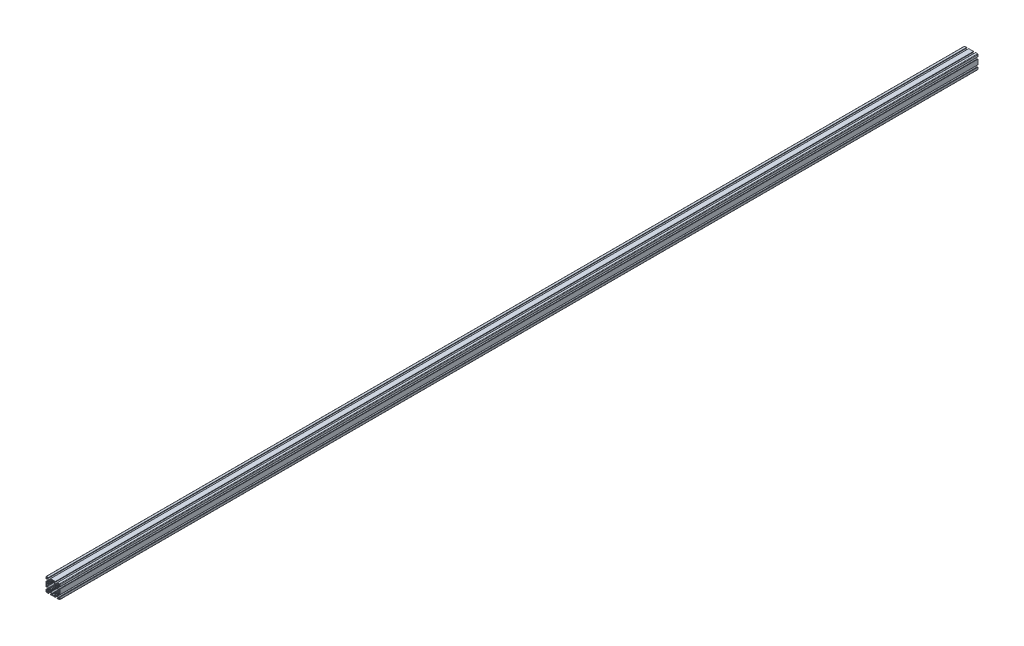
SolidWorks part; units mm, degrees
material "6105-T5 Aluminum"
ref_plane "Front Plane" through (0, 0, 0) normal (0, 0, 1) x (1, 0, 0)
ref_plane "Top Plane" through (0, 0, 0) normal (0, 1, 0) x (1, 0, 0)
ref_plane "Right Plane" through (0, 0, 0) normal (1, 0, 0) x (0, 0, -1)
sketch "Sketch1" plane through (0, 0, 0) normal (0, 0, 1) x (1, 0, 0)
  line L0 (-13.319, -39.4999) -> (-9.88, -39.4999)
  line L1 (-9.5, -39.8799) -> (-9.5, -43.3189)
  line L2 (-9.881, -43.6999) -> (-12.7, -43.6999)
  line L3 (-13.7, -42.6999) -> (-13.7, -39.8809)
  line L4 (39.4999, -43.3189) -> (39.4999, -39.8799)
  line L5 (39.8799, -39.4999) -> (43.3189, -39.4999)
  line L6 (43.6999, -39.8809) -> (43.6999, -42.6999)
  line L7 (42.6999, -43.6999) -> (39.8809, -43.6999)
  line L8 (39.8809, 13.7) -> (42.6999, 13.7)
  line L9 (43.6999, 12.7) -> (43.6999, 9.881)
  line L10 (43.3189, 9.5) -> (39.8799, 9.5)
  line L11 (39.4999, 9.88) -> (39.4999, 13.319)
  line L12 (-9.5, 13.319) -> (-9.5, 9.88)
  line L13 (-9.88, 9.5) -> (-13.319, 9.5)
  line L14 (-13.7, 9.881) -> (-13.7, 12.7)
  line L15 (-12.7, 13.7) -> (-9.881, 13.7)
  line L16 (-1.4942, -3.1981) -> (-2.4733, -3.9799)
  line L17 (-3.9799, -2.4733) -> (-3.1981, -1.4942)
  line L18 (-3.1981, 1.4942) -> (-3.9799, 2.4733)
  line L19 (-2.4733, 3.9799) -> (-1.4942, 3.1981)
  line L20 (1.4942, 3.1981) -> (2.4733, 3.9799)
  line L21 (3.9799, 2.4733) -> (3.1981, 1.4942)
  line L22 (3.1981, -1.4942) -> (3.9799, -2.4733)
  line L23 (2.4733, -3.9799) -> (1.4942, -3.1981)
  line L24 (28.5057, -3.1981) -> (27.5266, -3.9799)
  line L25 (26.02, -2.4733) -> (26.8018, -1.4942)
  line L26 (26.8018, 1.4942) -> (26.02, 2.4733)
  line L27 (27.5266, 3.9799) -> (28.5057, 3.1981)
  line L28 (31.4942, 3.1981) -> (32.4733, 3.9799)
  line L29 (33.9799, 2.4733) -> (33.1981, 1.4942)
  line L30 (33.1981, -1.4942) -> (33.9799, -2.4733)
  line L31 (32.4733, -3.9799) -> (31.4942, -3.1981)
  line L32 (-1.4942, -33.1981) -> (-2.4733, -33.9799)
  line L33 (-3.9799, -32.4733) -> (-3.1981, -31.4942)
  line L34 (-3.1981, -28.5057) -> (-3.9799, -27.5266)
  line L35 (-2.4733, -26.02) -> (-1.4942, -26.8018)
  line L36 (1.4942, -26.8018) -> (2.4733, -26.02)
  line L37 (3.9799, -27.5266) -> (3.1981, -28.5057)
  line L38 (3.1981, -31.4942) -> (3.9799, -32.4733)
  line L39 (2.4733, -33.9799) -> (1.4942, -33.1981)
  line L40 (28.5057, -33.1981) -> (27.5266, -33.9799)
  line L41 (26.02, -32.4733) -> (26.8018, -31.4942)
  line L42 (26.8018, -28.5057) -> (26.02, -27.5266)
  line L43 (27.5266, -26.02) -> (28.5057, -26.8018)
  line L44 (31.4942, -26.8018) -> (32.4733, -26.02)
  line L45 (33.9799, -27.5266) -> (33.1981, -28.5057)
  line L46 (33.1981, -31.4942) -> (33.9799, -32.4733)
  line L47 (32.4733, -33.9799) -> (31.4942, -33.1981)
  line L48 (42.7999, -10.95) -> (42.7999, -19.05)
  line L49 (42.2999, -19.55) -> (39.2681, -19.55)
  line L50 (38.2075, -19.9893) -> (34.178, -24.0188)
  line L51 (33.8244, -24.1653) -> (30.9499, -24.1653)
  line L52 (30.9499, -24.1653) -> (29.9999, -24.6753)
  line L53 (29.9999, -24.6753) -> (29.0499, -24.1653)
  line L54 (29.0499, -24.1653) -> (26.1653, -24.1653)
  line L55 (24.1653, -26.1653) -> (24.1653, -29.1124)
  line L56 (24.1653, -29.1124) -> (24.6753, -30.0624)
  line L57 (24.6753, -30.0624) -> (24.1653, -31.0124)
  line L58 (24.1653, -31.0124) -> (24.1653, -33.8244)
  line L59 (24.0188, -34.178) -> (19.9893, -38.2075)
  line L60 (19.55, -39.2681) -> (19.55, -42.2999)
  line L61 (19.05, -42.7999) -> (10.95, -42.7999)
  line L62 (10.45, -42.2999) -> (10.45, -39.2681)
  line L63 (10.0106, -38.2075) -> (5.9811, -34.178)
  line L64 (5.8347, -33.8244) -> (5.8347, -31.0124)
  line L65 (5.8347, -31.0124) -> (5.3247, -30.0624)
  line L66 (5.3247, -30.0624) -> (5.8347, -29.1124)
  line L67 (5.8347, -29.1124) -> (5.8347, -26.1653)
  line L68 (3.8347, -24.1653) -> (0.95, -24.1653)
  line L69 (0.95, -24.1653) -> (0, -24.6753)
  line L70 (0, -24.6753) -> (-0.95, -24.1653)
  line L71 (-0.95, -24.1653) -> (-3.8245, -24.1653)
  line L72 (-4.178, -24.0188) -> (-8.2075, -19.9893)
  line L73 (-9.2682, -19.55) -> (-12.3, -19.55)
  line L74 (-12.8, -19.05) -> (-12.8, -10.95)
  line L75 (-12.3, -10.45) -> (-9.2682, -10.45)
  line L76 (-8.2075, -10.0106) -> (-4.178, -5.9811)
  line L77 (-3.8245, -5.8347) -> (-0.95, -5.8347)
  line L78 (-0.95, -5.8347) -> (0, -5.3247)
  line L79 (0, -5.3247) -> (0.95, -5.8347)
  line L80 (0.95, -5.8347) -> (3.8347, -5.8347)
  line L81 (5.8347, -3.8347) -> (5.8347, -1.0125)
  line L82 (5.8347, -1.0125) -> (5.3247, -0.0625)
  line L83 (5.3247, -0.0625) -> (5.8347, 0.8875)
  line L84 (5.8347, 0.8875) -> (5.8347, 3.8245)
  line L85 (5.9811, 4.178) -> (10.0106, 8.2075)
  line L86 (10.45, 9.2682) -> (10.45, 12.3)
  line L87 (10.95, 12.8) -> (19.05, 12.8)
  line L88 (19.55, 12.3) -> (19.55, 9.2682)
  line L89 (19.9893, 8.2075) -> (24.0188, 4.178)
  line L90 (24.1653, 3.8245) -> (24.1653, 0.8875)
  line L91 (24.1653, 0.8875) -> (24.6753, -0.0625)
  line L92 (24.6753, -0.0625) -> (24.1653, -1.0125)
  line L93 (24.1653, -1.0125) -> (24.1653, -3.8347)
  line L94 (26.1653, -5.8347) -> (29.0499, -5.8347)
  line L95 (29.0499, -5.8347) -> (29.9999, -5.3247)
  line L96 (29.9999, -5.3247) -> (30.9499, -5.8347)
  line L97 (30.9499, -5.8347) -> (33.8244, -5.8347)
  line L98 (34.178, -5.9811) -> (38.2075, -10.0106)
  line L99 (39.2681, -10.45) -> (42.2999, -10.45)
  line L100 (-14.5, -25.9999) -> (-13.2425, -25.9999)
  line L101 (-12.7425, -25.4999) -> (-12.7425, -22.2674)
  line L102 (-12.2428, -21.75) -> (-10.2602, -21.75)
  line L103 (-9.9067, -21.8964) -> (-5.9811, -25.8219)
  line L104 (-5.8347, -26.1755) -> (-5.8347, -29.1124)
  line L105 (-5.8347, -29.1124) -> (-5.3247, -30.0624)
  line L106 (-5.3247, -30.0624) -> (-5.8347, -31.0124)
  line L107 (-5.8347, -31.0124) -> (-5.8347, -33.8244)
  line L108 (-5.9811, -34.178) -> (-9.9067, -38.1035)
  line L109 (-10.2602, -38.2499) -> (-12.2428, -38.2499)
  line L110 (-12.7425, -37.7325) -> (-12.7425, -34.4999)
  line L111 (-13.2425, -33.9999) -> (-14.5, -33.9999)
  line L112 (-15, -34.4999) -> (-15, -42.9999)
  line L113 (-13, -44.9999) -> (-4.5, -44.9999)
  line L114 (-4, -44.4999) -> (-4, -43.2424)
  line L115 (-4.5, -42.7424) -> (-7.7325, -42.7424)
  line L116 (-8.25, -42.2427) -> (-8.25, -40.2601)
  line L117 (-8.1035, -39.9066) -> (-4.178, -35.9811)
  line L118 (-3.8245, -35.8346) -> (-0.95, -35.8346)
  line L119 (-0.95, -35.8346) -> (0, -35.3246)
  line L120 (0, -35.3246) -> (0.95, -35.8346)
  line L121 (0.95, -35.8346) -> (3.8245, -35.8346)
  line L122 (4.178, -35.9811) -> (8.1035, -39.9066)
  line L123 (8.25, -40.2601) -> (8.25, -42.2427)
  line L124 (7.7325, -42.7424) -> (4.5, -42.7424)
  line L125 (4, -43.2424) -> (4, -44.4999)
  line L126 (4.5, -44.9999) -> (25.4999, -44.9999)
  line L127 (25.9999, -44.4999) -> (25.9999, -43.2424)
  line L128 (25.4999, -42.7424) -> (22.2674, -42.7424)
  line L129 (21.75, -42.2427) -> (21.75, -40.2601)
  line L130 (21.8964, -39.9066) -> (25.8219, -35.9811)
  line L131 (26.1755, -35.8346) -> (29.0499, -35.8346)
  line L132 (29.0499, -35.8346) -> (29.9999, -35.3246)
  line L133 (29.9999, -35.3246) -> (30.9499, -35.8346)
  line L134 (30.9499, -35.8346) -> (33.8244, -35.8346)
  line L135 (34.178, -35.9811) -> (38.1035, -39.9066)
  line L136 (38.2499, -40.2601) -> (38.2499, -42.2427)
  line L137 (37.7325, -42.7424) -> (34.4999, -42.7424)
  line L138 (33.9999, -43.2424) -> (33.9999, -44.4999)
  line L139 (34.4999, -44.9999) -> (42.9999, -44.9999)
  line L140 (44.9999, -42.9999) -> (44.9999, -34.4999)
  line L141 (44.4999, -33.9999) -> (43.2424, -33.9999)
  line L142 (42.7424, -34.4999) -> (42.7424, -37.7325)
  line L143 (42.2427, -38.2499) -> (40.2601, -38.2499)
  line L144 (39.9066, -38.1035) -> (35.9811, -34.178)
  line L145 (35.8346, -33.8244) -> (35.8346, -31.0124)
  line L146 (35.8346, -31.0124) -> (35.3246, -30.0624)
  line L147 (35.3246, -30.0624) -> (35.8346, -29.1124)
  line L148 (35.8346, -29.1124) -> (35.8346, -26.1755)
  line L149 (35.9811, -25.8219) -> (39.9066, -21.8964)
  line L150 (40.2601, -21.75) -> (42.2427, -21.75)
  line L151 (42.7424, -22.2674) -> (42.7424, -25.4999)
  line L152 (43.2424, -25.9999) -> (44.4999, -25.9999)
  line L153 (44.9999, -25.4999) -> (44.9999, -4.5)
  line L154 (44.4999, -4) -> (43.2424, -4)
  line L155 (42.7424, -4.5) -> (42.7424, -7.7325)
  line L156 (42.2427, -8.25) -> (40.2601, -8.25)
  line L157 (39.9066, -8.1035) -> (35.9811, -4.178)
  line L158 (35.8346, -3.8245) -> (35.8346, -1.0125)
  line L159 (35.8346, -1.0125) -> (35.3246, -0.0625)
  line L160 (35.3246, -0.0625) -> (35.8346, 0.8875)
  line L161 (35.8346, 0.8875) -> (35.8346, 3.8245)
  line L162 (35.9811, 4.178) -> (39.9066, 8.1035)
  line L163 (40.2601, 8.25) -> (42.2427, 8.25)
  line L164 (42.7424, 7.7325) -> (42.7424, 4.5)
  line L165 (43.2424, 4) -> (44.4999, 4)
  line L166 (44.9999, 4.5) -> (44.9999, 13)
  line L167 (42.9999, 15) -> (34.4999, 15)
  line L168 (33.9999, 14.5) -> (33.9999, 13.2425)
  line L169 (34.4999, 12.7425) -> (37.7325, 12.7425)
  line L170 (38.2499, 12.2428) -> (38.2499, 10.2602)
  line L171 (38.1035, 9.9067) -> (34.178, 5.9811)
  line L172 (33.8244, 5.8347) -> (30.9499, 5.8347)
  line L173 (30.9499, 5.8347) -> (29.9999, 5.3247)
  line L174 (29.9999, 5.3247) -> (29.0499, 5.8347)
  line L175 (29.0499, 5.8347) -> (26.1755, 5.8347)
  line L176 (25.8219, 5.9811) -> (21.8964, 9.9067)
  line L177 (21.75, 10.2602) -> (21.75, 12.2428)
  line L178 (22.2674, 12.7425) -> (25.4999, 12.7425)
  line L179 (25.9999, 13.2425) -> (25.9999, 14.5)
  line L180 (25.4999, 15) -> (4.5, 15)
  line L181 (4, 14.5) -> (4, 13.2425)
  line L182 (4.5, 12.7425) -> (7.7325, 12.7425)
  line L183 (8.25, 12.2428) -> (8.25, 10.2602)
  line L184 (8.1035, 9.9067) -> (4.178, 5.9811)
  line L185 (3.8245, 5.8347) -> (0.95, 5.8347)
  line L186 (0.95, 5.8347) -> (0, 5.3247)
  line L187 (0, 5.3247) -> (-0.95, 5.8347)
  line L188 (-0.95, 5.8347) -> (-3.8245, 5.8347)
  line L189 (-4.178, 5.9811) -> (-8.1035, 9.9067)
  line L190 (-8.25, 10.2602) -> (-8.25, 12.2428)
  line L191 (-7.7325, 12.7425) -> (-4.5, 12.7425)
  line L192 (-4, 13.2425) -> (-4, 14.5)
  line L193 (-4.5, 15) -> (-13, 15)
  line L194 (-15, 13) -> (-15, 4.5)
  line L195 (-14.5, 4) -> (-13.2425, 4)
  line L196 (-12.7425, 4.5) -> (-12.7425, 7.7325)
  line L197 (-12.2428, 8.25) -> (-10.2602, 8.25)
  line L198 (-9.9067, 8.1035) -> (-5.9811, 4.178)
  line L199 (-5.8347, 3.8245) -> (-5.8347, 0.8875)
  line L200 (-5.8347, 0.8875) -> (-5.3247, -0.0625)
  line L201 (-5.3247, -0.0625) -> (-5.8347, -1.0125)
  line L202 (-5.8347, -1.0125) -> (-5.8347, -3.8245)
  line L203 (-5.9811, -4.178) -> (-9.9067, -8.1035)
  line L204 (-10.2602, -8.25) -> (-12.2428, -8.25)
  line L205 (-12.7425, -7.7325) -> (-12.7425, -4.5)
  line L206 (-13.2425, -4) -> (-14.5, -4)
  line L207 (-15, -4.5) -> (-15, -25.4999)
  arc A0 (-13.319, -39.4999) -> (-13.7, -39.8809) centre (-13.319, -39.8809) ccw
  arc A1 (-9.5, -39.8799) -> (-9.88, -39.4999) centre (-9.88, -39.8799) ccw
  arc A2 (-9.881, -43.6999) -> (-9.5, -43.3189) centre (-9.881, -43.3189) ccw
  arc A3 (-13.7, -42.6999) -> (-12.7, -43.6999) centre (-12.7, -42.6999) ccw
  arc A4 (39.4999, -43.3189) -> (39.8809, -43.6999) centre (39.8809, -43.3189) ccw
  arc A5 (39.8799, -39.4999) -> (39.4999, -39.8799) centre (39.8799, -39.8799) ccw
  arc A6 (43.6999, -39.8809) -> (43.3189, -39.4999) centre (43.3189, -39.8809) ccw
  arc A7 (42.6999, -43.6999) -> (43.6999, -42.6999) centre (42.6999, -42.6999) ccw
  arc A8 (39.8809, 13.7) -> (39.4999, 13.319) centre (39.8809, 13.319) ccw
  arc A9 (43.6999, 12.7) -> (42.6999, 13.7) centre (42.6999, 12.7) ccw
  arc A10 (43.3189, 9.5) -> (43.6999, 9.881) centre (43.3189, 9.881) ccw
  arc A11 (39.4999, 9.88) -> (39.8799, 9.5) centre (39.8799, 9.88) ccw
  arc A12 (-9.5, 13.319) -> (-9.881, 13.7) centre (-9.881, 13.319) ccw
  arc A13 (-9.88, 9.5) -> (-9.5, 9.88) centre (-9.88, 9.88) ccw
  arc A14 (-13.7, 9.881) -> (-13.319, 9.5) centre (-13.319, 9.881) ccw
  arc A15 (-12.7, 13.7) -> (-13.7, 12.7) centre (-12.7, 12.7) ccw
  arc A16 (-1.4942, -3.1981) -> (1.4942, -3.1981) centre (0, 0) ccw
  arc A17 (-3.9799, -2.4733) -> (-2.4733, -3.9799) centre (-3.1422, -3.1422) ccw
  arc A18 (-3.1981, 1.4942) -> (-3.1981, -1.4942) centre (0, 0) ccw
  arc A19 (-2.4733, 3.9799) -> (-3.9799, 2.4733) centre (-3.1422, 3.1422) ccw
  arc A20 (1.4942, 3.1981) -> (-1.4942, 3.1981) centre (0, 0) ccw
  arc A21 (3.9799, 2.4733) -> (2.4733, 3.9799) centre (3.1422, 3.1422) ccw
  arc A22 (3.1981, -1.4942) -> (3.1981, 1.4942) centre (0, 0) ccw
  arc A23 (2.4733, -3.9799) -> (3.9799, -2.4733) centre (3.1422, -3.1422) ccw
  arc A24 (28.5057, -3.1981) -> (31.4942, -3.1981) centre (29.9999, 0) ccw
  arc A25 (26.02, -2.4733) -> (27.5266, -3.9799) centre (26.8577, -3.1422) ccw
  arc A26 (26.8018, 1.4942) -> (26.8018, -1.4942) centre (29.9999, 0) ccw
  arc A27 (27.5266, 3.9799) -> (26.02, 2.4733) centre (26.8577, 3.1422) ccw
  arc A28 (31.4942, 3.1981) -> (28.5057, 3.1981) centre (29.9999, 0) ccw
  arc A29 (33.9799, 2.4733) -> (32.4733, 3.9799) centre (33.1422, 3.1422) ccw
  arc A30 (33.1981, -1.4942) -> (33.1981, 1.4942) centre (29.9999, 0) ccw
  arc A31 (32.4733, -3.9799) -> (33.9799, -2.4733) centre (33.1422, -3.1422) ccw
  arc A32 (-1.4942, -33.1981) -> (1.4942, -33.1981) centre (0, -29.9999) ccw
  arc A33 (-3.9799, -32.4733) -> (-2.4733, -33.9799) centre (-3.1422, -33.1422) ccw
  arc A34 (-3.1981, -28.5057) -> (-3.1981, -31.4942) centre (0, -29.9999) ccw
  arc A35 (-2.4733, -26.02) -> (-3.9799, -27.5266) centre (-3.1422, -26.8577) ccw
  arc A36 (1.4942, -26.8018) -> (-1.4942, -26.8018) centre (0, -29.9999) ccw
  arc A37 (3.9799, -27.5266) -> (2.4733, -26.02) centre (3.1422, -26.8577) ccw
  arc A38 (3.1981, -31.4942) -> (3.1981, -28.5057) centre (0, -29.9999) ccw
  arc A39 (2.4733, -33.9799) -> (3.9799, -32.4733) centre (3.1422, -33.1422) ccw
  arc A40 (28.5057, -33.1981) -> (31.4942, -33.1981) centre (29.9999, -29.9999) ccw
  arc A41 (26.02, -32.4733) -> (27.5266, -33.9799) centre (26.8577, -33.1422) ccw
  arc A42 (26.8018, -28.5057) -> (26.8018, -31.4942) centre (29.9999, -29.9999) ccw
  arc A43 (27.5266, -26.02) -> (26.02, -27.5266) centre (26.8577, -26.8577) ccw
  arc A44 (31.4942, -26.8018) -> (28.5057, -26.8018) centre (29.9999, -29.9999) ccw
  arc A45 (33.9799, -27.5266) -> (32.4733, -26.02) centre (33.1422, -26.8577) ccw
  arc A46 (33.1981, -31.4942) -> (33.1981, -28.5057) centre (29.9999, -29.9999) ccw
  arc A47 (32.4733, -33.9799) -> (33.9799, -32.4733) centre (33.1422, -33.1422) ccw
  arc A48 (42.7999, -10.95) -> (42.2999, -10.45) centre (42.2999, -10.95) ccw
  arc A49 (42.2999, -19.55) -> (42.7999, -19.05) centre (42.2999, -19.05) ccw
  arc A50 (39.2681, -19.55) -> (38.2075, -19.9893) centre (39.2681, -21.05) ccw
  arc A51 (33.8244, -24.1653) -> (34.178, -24.0188) centre (33.8244, -23.6653) ccw
  arc A52 (26.1653, -24.1653) -> (24.1653, -26.1653) centre (26.1653, -26.1653) ccw
  arc A53 (24.0188, -34.178) -> (24.1653, -33.8244) centre (23.6653, -33.8244) ccw
  arc A54 (19.9893, -38.2075) -> (19.55, -39.2681) centre (21.05, -39.2681) ccw
  arc A55 (19.05, -42.7999) -> (19.55, -42.2999) centre (19.05, -42.2999) ccw
  arc A56 (10.45, -42.2999) -> (10.95, -42.7999) centre (10.95, -42.2999) ccw
  arc A57 (10.45, -39.2681) -> (10.0106, -38.2075) centre (8.95, -39.2681) ccw
  arc A58 (5.8347, -33.8244) -> (5.9811, -34.178) centre (6.3347, -33.8244) ccw
  arc A59 (5.8347, -26.1653) -> (3.8347, -24.1653) centre (3.8347, -26.1653) ccw
  arc A60 (-4.178, -24.0188) -> (-3.8245, -24.1653) centre (-3.8245, -23.6653) ccw
  arc A61 (-8.2075, -19.9893) -> (-9.2682, -19.55) centre (-9.2682, -21.05) ccw
  arc A62 (-12.8, -19.05) -> (-12.3, -19.55) centre (-12.3, -19.05) ccw
  arc A63 (-12.3, -10.45) -> (-12.8, -10.95) centre (-12.3, -10.95) ccw
  arc A64 (-9.2682, -10.45) -> (-8.2075, -10.0106) centre (-9.2682, -8.95) ccw
  arc A65 (-3.8245, -5.8347) -> (-4.178, -5.9811) centre (-3.8245, -6.3347) ccw
  arc A66 (3.8347, -5.8347) -> (5.8347, -3.8347) centre (3.8347, -3.8347) ccw
  arc A67 (5.9811, 4.178) -> (5.8347, 3.8245) centre (6.3347, 3.8245) ccw
  arc A68 (10.0106, 8.2075) -> (10.45, 9.2682) centre (8.95, 9.2682) ccw
  arc A69 (10.95, 12.8) -> (10.45, 12.3) centre (10.95, 12.3) ccw
  arc A70 (19.55, 12.3) -> (19.05, 12.8) centre (19.05, 12.3) ccw
  arc A71 (19.55, 9.2682) -> (19.9893, 8.2075) centre (21.05, 9.2682) ccw
  arc A72 (24.1653, 3.8245) -> (24.0188, 4.178) centre (23.6653, 3.8245) ccw
  arc A73 (24.1653, -3.8347) -> (26.1653, -5.8347) centre (26.1653, -3.8347) ccw
  arc A74 (34.178, -5.9811) -> (33.8244, -5.8347) centre (33.8244, -6.3347) ccw
  arc A75 (38.2075, -10.0106) -> (39.2681, -10.45) centre (39.2681, -8.95) ccw
  arc A76 (-13.2425, -25.9999) -> (-12.7425, -25.4999) centre (-13.2425, -25.4999) ccw
  arc A77 (-12.2428, -21.75) -> (-12.7425, -22.2674) centre (-12.2428, -22.25) ccw
  arc A78 (-9.9067, -21.8964) -> (-10.2602, -21.75) centre (-10.2602, -22.25) ccw
  arc A79 (-5.8347, -26.1755) -> (-5.9811, -25.8219) centre (-6.3347, -26.1755) ccw
  arc A80 (-5.9811, -34.178) -> (-5.8347, -33.8244) centre (-6.3347, -33.8244) ccw
  arc A81 (-10.2602, -38.2499) -> (-9.9067, -38.1035) centre (-10.2602, -37.7499) ccw
  arc A82 (-12.7425, -37.7325) -> (-12.2428, -38.2499) centre (-12.2428, -37.7499) ccw
  arc A83 (-12.7425, -34.4999) -> (-13.2425, -33.9999) centre (-13.2425, -34.4999) ccw
  arc A84 (-14.5, -33.9999) -> (-15, -34.4999) centre (-14.5, -34.4999) ccw
  arc A85 (-15, -42.9999) -> (-13, -44.9999) centre (-13, -42.9999) ccw
  arc A86 (-4.5, -44.9999) -> (-4, -44.4999) centre (-4.5, -44.4999) ccw
  arc A87 (-4, -43.2424) -> (-4.5, -42.7424) centre (-4.5, -43.2424) ccw
  arc A88 (-8.25, -42.2427) -> (-7.7325, -42.7424) centre (-7.75, -42.2427) ccw
  arc A89 (-8.1035, -39.9066) -> (-8.25, -40.2601) centre (-7.75, -40.2601) ccw
  arc A90 (-3.8245, -35.8346) -> (-4.178, -35.9811) centre (-3.8245, -36.3346) ccw
  arc A91 (4.178, -35.9811) -> (3.8245, -35.8346) centre (3.8245, -36.3346) ccw
  arc A92 (8.25, -40.2601) -> (8.1035, -39.9066) centre (7.75, -40.2601) ccw
  arc A93 (7.7325, -42.7424) -> (8.25, -42.2427) centre (7.75, -42.2427) ccw
  arc A94 (4.5, -42.7424) -> (4, -43.2424) centre (4.5, -43.2424) ccw
  arc A95 (4, -44.4999) -> (4.5, -44.9999) centre (4.5, -44.4999) ccw
  arc A96 (25.4999, -44.9999) -> (25.9999, -44.4999) centre (25.4999, -44.4999) ccw
  arc A97 (25.9999, -43.2424) -> (25.4999, -42.7424) centre (25.4999, -43.2424) ccw
  arc A98 (21.75, -42.2427) -> (22.2674, -42.7424) centre (22.25, -42.2427) ccw
  arc A99 (21.8964, -39.9066) -> (21.75, -40.2601) centre (22.25, -40.2601) ccw
  arc A100 (26.1755, -35.8346) -> (25.8219, -35.9811) centre (26.1755, -36.3346) ccw
  arc A101 (34.178, -35.9811) -> (33.8244, -35.8346) centre (33.8244, -36.3346) ccw
  arc A102 (38.2499, -40.2601) -> (38.1035, -39.9066) centre (37.7499, -40.2601) ccw
  arc A103 (37.7325, -42.7424) -> (38.2499, -42.2427) centre (37.7499, -42.2427) ccw
  arc A104 (34.4999, -42.7424) -> (33.9999, -43.2424) centre (34.4999, -43.2424) ccw
  arc A105 (33.9999, -44.4999) -> (34.4999, -44.9999) centre (34.4999, -44.4999) ccw
  arc A106 (42.9999, -44.9999) -> (44.9999, -42.9999) centre (42.9999, -42.9999) ccw
  arc A107 (44.9999, -34.4999) -> (44.4999, -33.9999) centre (44.4999, -34.4999) ccw
  arc A108 (43.2424, -33.9999) -> (42.7424, -34.4999) centre (43.2424, -34.4999) ccw
  arc A109 (42.2427, -38.2499) -> (42.7424, -37.7325) centre (42.2427, -37.7499) ccw
  arc A110 (39.9066, -38.1035) -> (40.2601, -38.2499) centre (40.2601, -37.7499) ccw
  arc A111 (35.8346, -33.8244) -> (35.9811, -34.178) centre (36.3346, -33.8244) ccw
  arc A112 (35.9811, -25.8219) -> (35.8346, -26.1755) centre (36.3346, -26.1755) ccw
  arc A113 (40.2601, -21.75) -> (39.9066, -21.8964) centre (40.2601, -22.25) ccw
  arc A114 (42.7424, -22.2674) -> (42.2427, -21.75) centre (42.2427, -22.25) ccw
  arc A115 (42.7424, -25.4999) -> (43.2424, -25.9999) centre (43.2424, -25.4999) ccw
  arc A116 (44.4999, -25.9999) -> (44.9999, -25.4999) centre (44.4999, -25.4999) ccw
  arc A117 (44.9999, -4.5) -> (44.4999, -4) centre (44.4999, -4.5) ccw
  arc A118 (43.2424, -4) -> (42.7424, -4.5) centre (43.2424, -4.5) ccw
  arc A119 (42.2427, -8.25) -> (42.7424, -7.7325) centre (42.2427, -7.75) ccw
  arc A120 (39.9066, -8.1035) -> (40.2601, -8.25) centre (40.2601, -7.75) ccw
  arc A121 (35.8346, -3.8245) -> (35.9811, -4.178) centre (36.3346, -3.8245) ccw
  arc A122 (35.9811, 4.178) -> (35.8346, 3.8245) centre (36.3346, 3.8245) ccw
  arc A123 (40.2601, 8.25) -> (39.9066, 8.1035) centre (40.2601, 7.75) ccw
  arc A124 (42.7424, 7.7325) -> (42.2427, 8.25) centre (42.2427, 7.75) ccw
  arc A125 (42.7424, 4.5) -> (43.2424, 4) centre (43.2424, 4.5) ccw
  arc A126 (44.4999, 4) -> (44.9999, 4.5) centre (44.4999, 4.5) ccw
  arc A127 (44.9999, 13) -> (42.9999, 15) centre (42.9999, 13) ccw
  arc A128 (34.4999, 15) -> (33.9999, 14.5) centre (34.4999, 14.5) ccw
  arc A129 (33.9999, 13.2425) -> (34.4999, 12.7425) centre (34.4999, 13.2425) ccw
  arc A130 (38.2499, 12.2428) -> (37.7325, 12.7425) centre (37.7499, 12.2428) ccw
  arc A131 (38.1035, 9.9067) -> (38.2499, 10.2602) centre (37.7499, 10.2602) ccw
  arc A132 (33.8244, 5.8347) -> (34.178, 5.9811) centre (33.8244, 6.3347) ccw
  arc A133 (25.8219, 5.9811) -> (26.1755, 5.8347) centre (26.1755, 6.3347) ccw
  arc A134 (21.75, 10.2602) -> (21.8964, 9.9067) centre (22.25, 10.2602) ccw
  arc A135 (22.2674, 12.7425) -> (21.75, 12.2428) centre (22.25, 12.2428) ccw
  arc A136 (25.4999, 12.7425) -> (25.9999, 13.2425) centre (25.4999, 13.2425) ccw
  arc A137 (25.9999, 14.5) -> (25.4999, 15) centre (25.4999, 14.5) ccw
  arc A138 (4.5, 15) -> (4, 14.5) centre (4.5, 14.5) ccw
  arc A139 (4, 13.2425) -> (4.5, 12.7425) centre (4.5, 13.2425) ccw
  arc A140 (8.25, 12.2428) -> (7.7325, 12.7425) centre (7.75, 12.2428) ccw
  arc A141 (8.1035, 9.9067) -> (8.25, 10.2602) centre (7.75, 10.2602) ccw
  arc A142 (3.8245, 5.8347) -> (4.178, 5.9811) centre (3.8245, 6.3347) ccw
  arc A143 (-4.178, 5.9811) -> (-3.8245, 5.8347) centre (-3.8245, 6.3347) ccw
  arc A144 (-8.25, 10.2602) -> (-8.1035, 9.9067) centre (-7.75, 10.2602) ccw
  arc A145 (-7.7325, 12.7425) -> (-8.25, 12.2428) centre (-7.75, 12.2428) ccw
  arc A146 (-4.5, 12.7425) -> (-4, 13.2425) centre (-4.5, 13.2425) ccw
  arc A147 (-4, 14.5) -> (-4.5, 15) centre (-4.5, 14.5) ccw
  arc A148 (-13, 15) -> (-15, 13) centre (-13, 13) ccw
  arc A149 (-15, 4.5) -> (-14.5, 4) centre (-14.5, 4.5) ccw
  arc A150 (-13.2425, 4) -> (-12.7425, 4.5) centre (-13.2425, 4.5) ccw
  arc A151 (-12.2428, 8.25) -> (-12.7425, 7.7325) centre (-12.2428, 7.75) ccw
  arc A152 (-9.9067, 8.1035) -> (-10.2602, 8.25) centre (-10.2602, 7.75) ccw
  arc A153 (-5.8347, 3.8245) -> (-5.9811, 4.178) centre (-6.3347, 3.8245) ccw
  arc A154 (-5.9811, -4.178) -> (-5.8347, -3.8245) centre (-6.3347, -3.8245) ccw
  arc A155 (-10.2602, -8.25) -> (-9.9067, -8.1035) centre (-10.2602, -7.75) ccw
  arc A156 (-12.7425, -7.7325) -> (-12.2428, -8.25) centre (-12.2428, -7.75) ccw
  arc A157 (-12.7425, -4.5) -> (-13.2425, -4) centre (-13.2425, -4.5) ccw
  arc A158 (-14.5, -4) -> (-15, -4.5) centre (-14.5, -4.5) ccw
  arc A159 (-15, -25.4999) -> (-14.5, -25.9999) centre (-14.5, -25.4999) ccw
extrude "Extrude1" add sketch "Sketch1" against normal blind 4000
